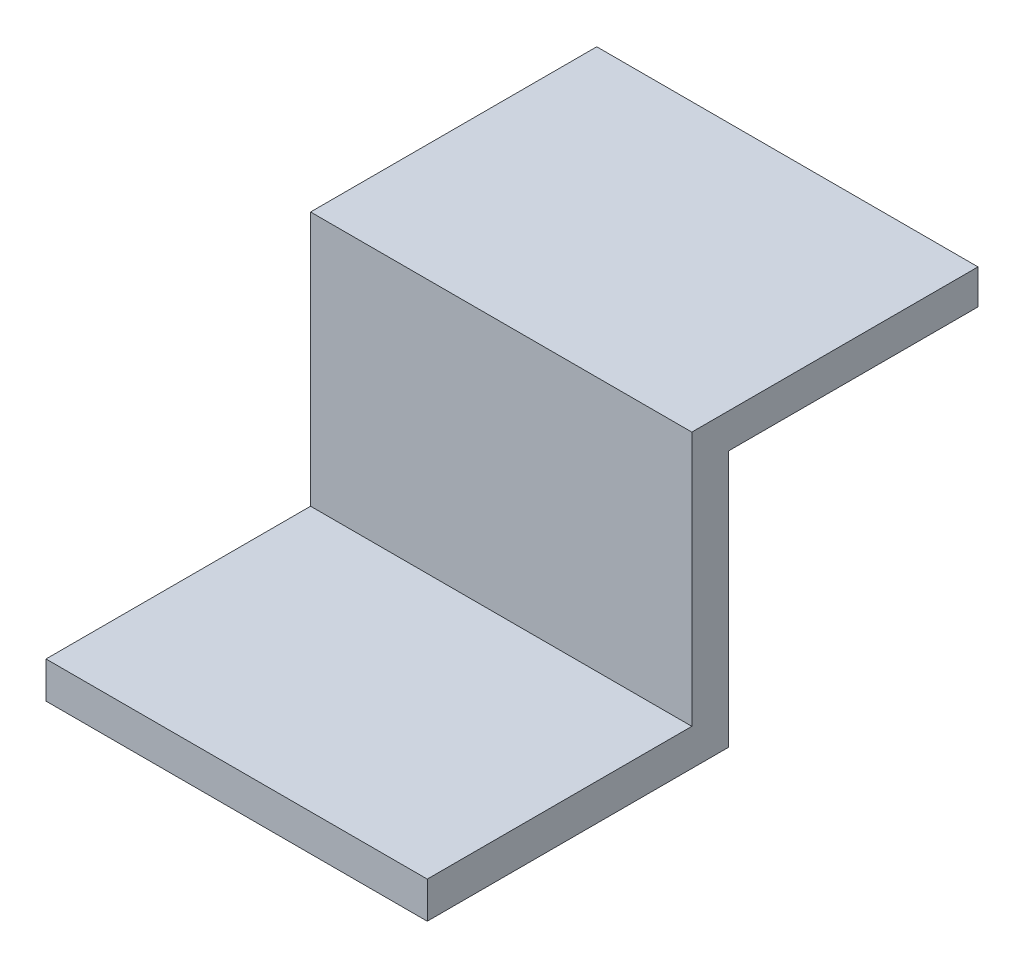
SolidWorks part; units mm, degrees
ref_plane "Front Plane" through (0, 0, 0) normal (0, 0, 1) x (1, 0, 0)
ref_plane "Top Plane" through (0, 0, 0) normal (0, 1, 0) x (1, 0, 0)
ref_plane "Right Plane" through (0, 0, 0) normal (1, 0, 0) x (0, 0, -1)
sketch "Sketch10" plane through (0, 0, 0) normal (1, 0, 0) x (0, 0, -1)
  line L0 (52.3533, 44.6272) -> (52.3533, 0)
  line L1 (52.3533, 0) -> (0, 0)
  line L2 (0, 0) -> (0, 6.35)
  line L3 (0, 6.35) -> (46.0033, 6.35)
  line L4 (46.0033, 6.35) -> (46.0033, 50.6588)
  line L5 (46.0033, 50.6588) -> (52.3533, 50.6588)
  line L7 (52.3533, 50.6588) -> (95.7628, 50.6588)
  line L9 (52.3533, 44.6272) -> (95.7628, 44.6272)
  line L10 (95.7628, 50.6588) -> (95.7628, 44.6272)
extrude "Extrude4" add sketch "Sketch10" against normal blind 66.294
ref_plane "Plane3" through (0, 3.2941, 3.1728) normal (0, -0.7202, -0.6937) x (1, 0, 0)
sketch "Sketch11" plane through (0, 3.2941, 3.1728) normal (0, -0.7202, -0.6937) x (1, 0, 0)
  line L0 (-33.147, -68.2766) -> (-33.147, -4.4051)
  line L1 (-66.294, -68.2766) -> (0, -68.2766) construction
  line L4 (-66.294, -4.4051) -> (0, -4.4051) construction
